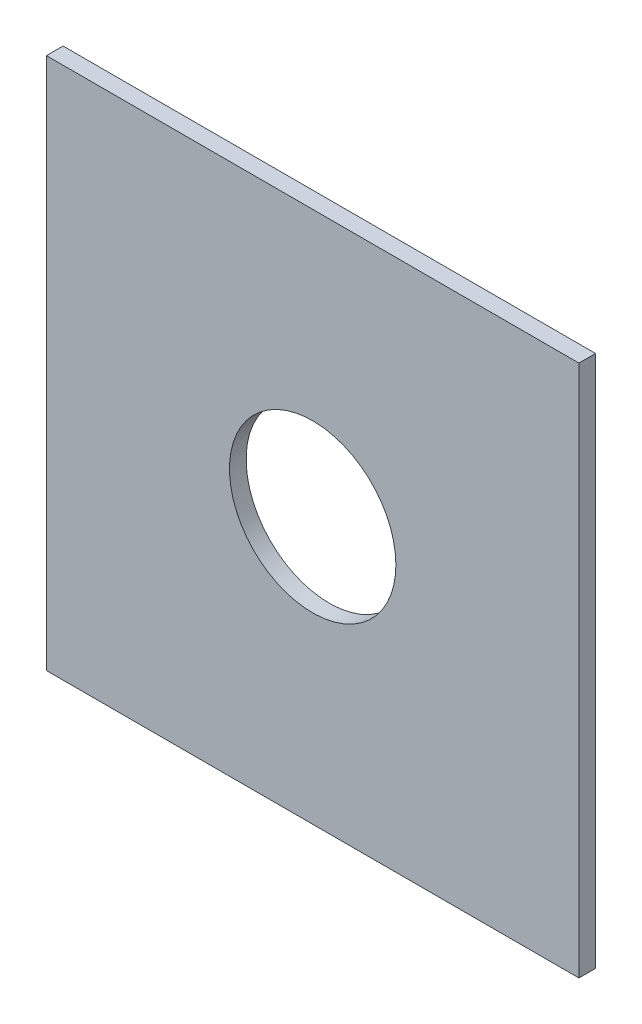
SolidWorks part; units mm, degrees
ref_plane "Alzado" through (0, 0, 0) normal (0, 0, 1) x (1, 0, 0)
ref_plane "Planta" through (0, 0, 0) normal (0, 1, 0) x (1, 0, 0)
ref_plane "Vista lateral" through (0, 0, 0) normal (1, 0, 0) x (0, 0, -1)
sketch "Croquis1" plane through (0, 0, 0) normal (0, 0, 1) x (1, 0, 0)
  line L1 (-80, 80) -> (80, 80)
  line L2 (-80, 80) -> (-80, -80)
  line L3 (-80, -80) -> (80, -80)
  line L4 (80, 80) -> (80, -80)
  line L5 (-80, 80) -> (80, -80) construction
  line L6 (-80, -80) -> (80, 80) construction
  point P0 (0, 0)
  dimension "D1" = 160
  dimension "D2" = 160
extrude "Saliente-Extruir1" add sketch "Croquis1" along normal blind 5
sketch "Croquis2" plane through (0, 0, 5) normal (0, 0, 1) x (1, 0, 0)
  circle A0 centre (0, 0) radius 25
  dimension "D1" = 50
extrude "Cortar-Extruir1" cut sketch "Croquis2" against normal blind 10
